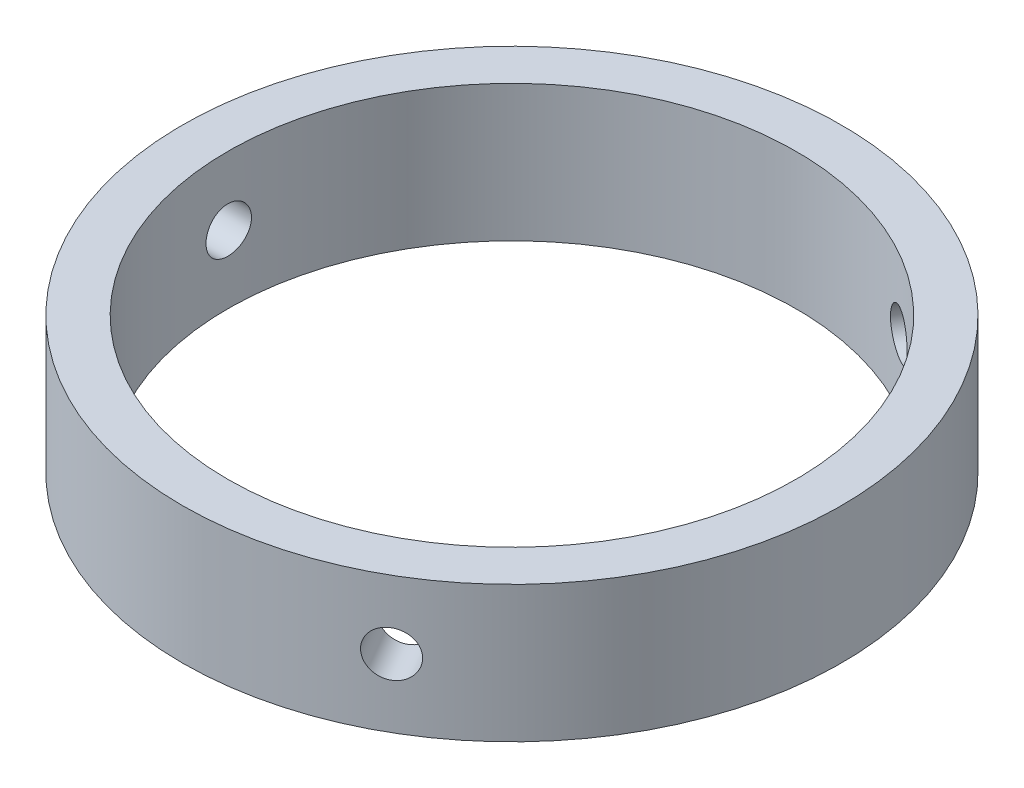
SolidWorks part; units mm, degrees
ref_plane "Front Plane" through (0, 0, 0) normal (0, 0, 1) x (1, 0, 0)
ref_plane "Top Plane" through (0, 0, 0) normal (0, 1, 0) x (1, 0, 0)
ref_plane "Right Plane" through (0, 0, 0) normal (1, 0, 0) x (0, 0, -1)
sketch "Sketch1" plane through (0, 0, 0) normal (0, 1, 0) x (1, 0, 0)
  circle A0 centre (0, 0) radius 39.6875
  circle A1 centre (0, 0) radius 46.0375
  dimension "D1" = 79.375
  dimension "D2" = 6.35
extrude "Boss-Extrude1" add sketch "Sketch1" along normal blind 19.05
sketch "Sketch2" plane through (0, 0, 0) normal (0, 1, 0) x (1, 0, 0)
  line L0 (0, 0) -> (47.3416, -27.3327) construction
  line L1 (0, 0) -> (-47.2654, -27.2887) construction
  line L2 (0, 0) -> (0, 48.8431) construction
  dimension "D1" = 120
  dimension "D2" = 120
ref_plane "Plane3" through (0, 0, 0) normal (1, 0, 0) x (0, 0, -1)
ref_plane "Plane4" through (0, 0, 0) normal (-0.5, 0, -0.866) x (-0.866, 0, 0.5)
ref_plane "Plane5" through (0, 0, 0) normal (-0.5, 0, 0.866) x (0.866, 0, 0.5)
sketch "Sketch3" plane through (0, 0, 0) normal (1, 0, 0) x (0, 0, -1)
  circle A0 centre (0, 9.525) radius 3.175
  dimension "D1" = 6.35
  dimension "D2" = 9.525
sketch "Sketch4" plane through (0, 0, 0) normal (-0.5, 0, 0.866) x (0.866, 0, 0.5)
  circle A0 centre (0, 9.525) radius 3.175
  dimension "D1" = 6.35
sketch "Sketch5" plane through (0, 0, 0) normal (-0.5, 0, -0.866) x (-0.866, 0, 0.5)
  circle A0 centre (0, 9.525) radius 3.175
  dimension "D1" = 6.35
extrude "Cut-Extrude1" cut sketch "Sketch4" against normal blind 76.2 contours A0
extrude "Cut-Extrude2" cut sketch "Sketch5" against normal blind 76.2
extrude "Cut-Extrude3" cut sketch "Sketch3" against normal blind 76.2
